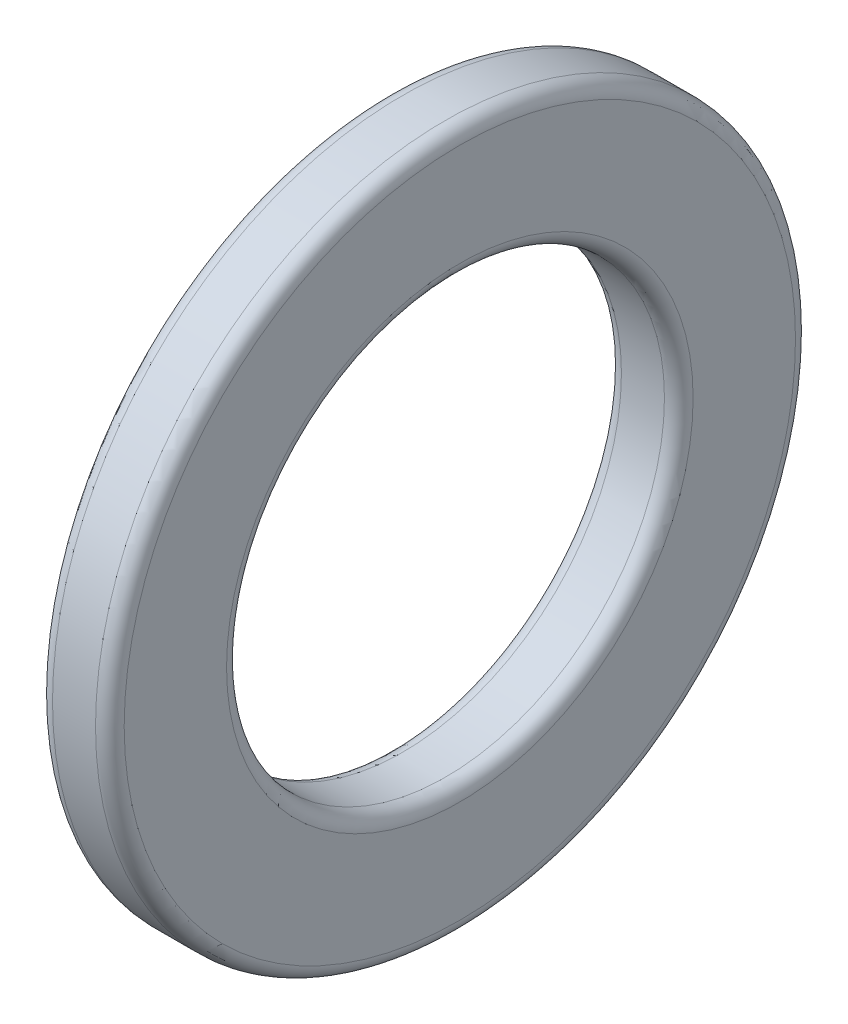
SolidWorks part; units mm, degrees
ref_plane "Front Plane" through (0, 0, 0) normal (0, 0, 1) x (1, 0, 0)
ref_plane "Top Plane" through (0, 0, 0) normal (0, 1, 0) x (1, 0, 0)
ref_plane "Right Plane" through (0, 0, 0) normal (1, 0, 0) x (0, 0, -1)
sketch "Sketch3" plane through (0, 0, 0) normal (0, 0, 1) x (1, 0, 0)
  line L0 (-0.8128, 0) -> (0.8128, 0) construction
  line L1 (0, -7.9375) -> (0, 7.9375) construction
  line L2 (0, -4.9657) -> (0, 4.9657) construction
  line L4 (0.8128, -7.9375) -> (-0.8128, -7.9375)
  line L5 (0.8128, -7.9375) -> (0.8128, 7.9375)
  line L6 (0.8128, 7.9375) -> (-0.8128, 7.9375)
  line L7 (-0.8128, -7.9375) -> (-0.8128, 7.9375)
  line L8 (0, 7.9375) -> (0, -7.9375) construction
  line L9 (0.8128, 0) -> (-0.8128, 0) construction
  point P0 (0, 0)
  point P4 (0, 0)
  point P8 (0, 0)
  point P11 (0, 0)
  dimension "ID" = 9.9314
  dimension "OD" = 15.875
  dimension "Thickness" = 1.6256
sketch "Sketch1" plane through (0, 0, 0) normal (1, 0, 0) x (0, 0, -1)
  circle A0 centre (0, 0) radius 7.9375
  circle A1 centre (0, 0) radius 4.9657
extrude "Boss-Extrude1" add sketch "Sketch1" along normal mid plane 1.6256
fillet "Fillet1" radius 0.3251 4 edges at (0.8128, 0, -7.9375) (-0.8128, 0, -7.9375) (0.8128, 0, -4.9657) (-0.8128, 0, -4.9657)
sketch "Sketch4" plane through (-0.8128, 0, 0) normal (-1, 0, 0) x (0, 0, 1)
  line L0 (0, -7.9375) -> (0, 7.9375) construction
  line L1 (0, -7.9375) -> (0, 7.9375) construction
  circle A0 centre (0, 0) radius 4.9657 construction
  circle A1 centre (0, 0) radius 7.9375 construction
  circle A2 centre (0, 0) radius 4.9657 construction
  circle A3 centre (0, 0) radius 7.9375 construction
  point P0 (0, -4.9657)
  point P1 (0, 4.9657)
  point P5 (-7.9375, 0)
  point P9 (-4.9657, 0)
  point P10 (4.9657, 0)
  point P11 (7.9375, 0)
equation "\"D1@Boss-Extrude1\" = \"Thickness@Sketch3\""
equation "\"D1@Fillet1\"=\"Thickness@Sketch3\"*.2"
